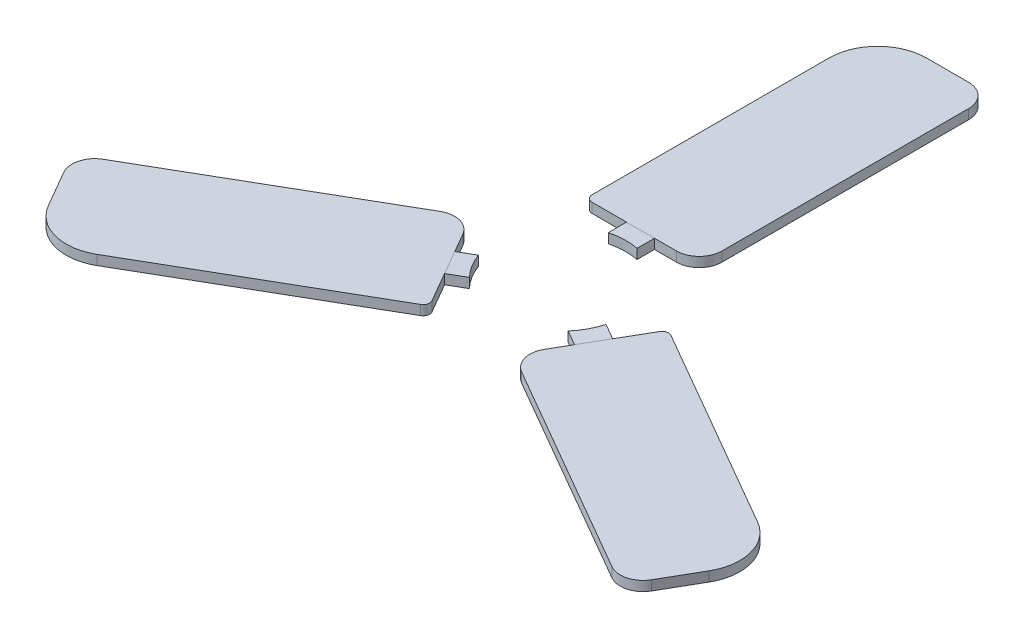
SolidWorks part; units mm, degrees
ref_plane "Front Plane" through (0, 0, 0) normal (0, 0, 1) x (1, 0, 0)
ref_plane "Top Plane" through (0, 0, 0) normal (0, 1, 0) x (1, 0, 0)
ref_plane "Right Plane" through (0, 0, 0) normal (1, 0, 0) x (0, 0, -1)
sketch "Sketch1" plane through (0, 0, 0) normal (0, 1, 0) x (1, 0, 0)
  line L0 (0, 0) -> (-105.994, 0)
  line L1 (-125.994, 20) -> (-125.994, 750)
  line L2 (24.006, 900) -> (154.006, 900)
  line L3 (224.006, 830) -> (224.006, 70)
  line L4 (154.006, 0) -> (0, 0)
  arc A0 (-125.994, 750) -> (24.006, 900) centre (24.006, 750) cw
  arc A1 (224.006, 70) -> (154.006, 0) centre (154.006, 70) cw
  arc A2 (154.006, 900) -> (224.006, 830) centre (154.006, 830) cw
  arc A3 (-105.994, 0) -> (-125.994, 20) centre (-105.994, 20) cw
  point P8 (-125.994, 900)
  point P13 (224.006, 900)
  point P16 (-125.994, 0)
  dimension "D3" = 150
  dimension "D4" = 70
  dimension "D5" = 20
  dimension "D1" = 900
  dimension "D2" = 350
sketch "Sketch2" plane through (0, 0, 0) normal (0, 1, 0) x (1, 0, 0)
  line L3 (49.006, -99.7994) -> (49.006, -100)
  circle A0 centre (49.006, -250) radius 150.2006
  dimension "D1" = 150
extrude "Boss-Extrude1" add sketch "Sketch1" along normal blind 30
extrude "Boss-Extrude2" add sketch "Sketch2" along normal blind 30 contours A0
pattern_circular "CirPattern2" count 3 over 360 about axis through (49.006, 0, 250) along (0, 1, 0) of "Boss-Extrude1"
sketch "Sketch3" plane through (0, 30, 0) normal (0, 1, 0) x (1, 0, 0)
  line L0 (0, -108.0189) -> (0, 0)
  line L1 (0, 0) -> (86.0738, 0)
  line L2 (-105.994, 0) -> (154.006, 0) construction
  line L3 (86.0738, 0) -> (86.0738, -104.4453)
  circle A0 centre (49.006, -250) radius 150.2006 construction
  circle A2 centre (49.006, -250) radius 150.2006
  arc A3 (86.0738, -104.4453) -> (0, -108.0189) centre (49.006, -250) ccw
  dimension "D1" = 0
extrude "Boss-Extrude4" add sketch "Sketch3" against normal blind 30 separate body
pattern_circular "CirPattern3" count 3 over 360 about axis through (49.006, 0, 250) along (0, 1, 0) of bodies 107
sketch "Sketch4" plane through (0, 30, 0) normal (0, 1, 0) x (1, 0, 0)
  circle A1 centre (49.006, -250) radius 150.2006
  circle A2 centre (49.006, -250) radius 150.2006
  dimension "D1" = 0
sketch "Sketch6" plane through (0, 30, 0) normal (0, 1, 0) x (1, 0, 0)
  circle A0 centre (49.006, -250) radius 200
  dimension "D1" = 400
extrude "Cut-Extrude1" cut sketch "Sketch6" against normal blind 30
